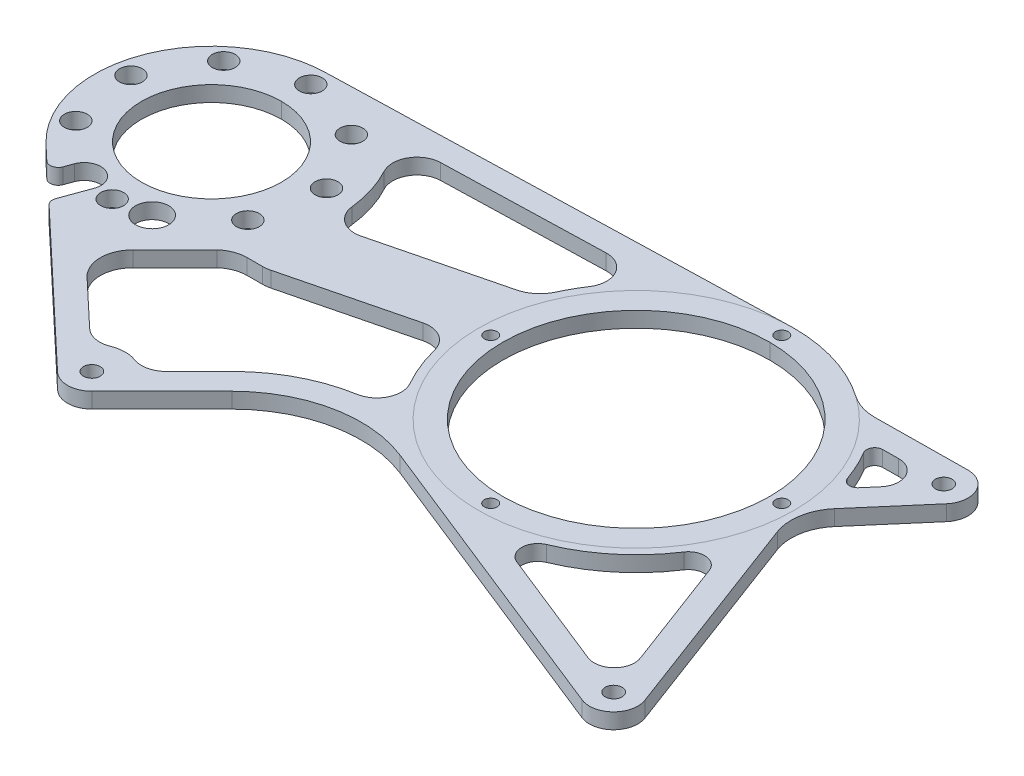
SolidWorks part; units mm, degrees
material "6061-T6 (SS)"
ref_plane "X-Y Datum" through (0, 0, 0) normal (0, 0, 1) x (1, 0, 0)
ref_plane "X-Z Datum" through (0, 0, 0) normal (0, 1, 0) x (1, 0, 0)
ref_plane "Y-Z Datum" through (0, 0, 0) normal (1, 0, 0) x (0, 0, -1)
sketch "Master Sketch " plane through (0, 0, 0) normal (0, 1, 0) x (1, 0, 0)
  line L0 (0, 0) -> (116.84, 0) construction
  line L1 (0, 0) -> (-54.61, 0) construction
  line L2 (116.84, 0) -> (228.6, 0) construction
  line L3 (228.6, 0) -> (228.6, 165.1) construction
  line L4 (123.19, 0) -> (123.19, 116.0018) construction
  line L5 (-54.61, 0) -> (-414.02, 0) construction
  line L6 (-54.61, 0) -> (-54.61, 127) construction
  line L7 (123.19, 168.4528) -> (123.19, 177.9778) construction
  line L8 (123.19, 116.0018) -> (228.6, 165.1) construction
  line L9 (123.19, 116.0018) -> (228.6, 0) construction
  line L10 (0, 0) -> (123.19, 116.0018) construction
  line L11 (0, 0) -> (-54.61, 127) construction
  line L12 (-54.61, 127) -> (123.19, 116.0018) construction
  line L13 (-54.61, 127) -> (228.6, 165.1) construction
  line L14 (0, 0) -> (0, 123.622) construction
  line L15 (-86.1521, 93.553) -> (-6.535, 18.4704)
  line L16 (-54.61, 172.974) -> (123.19, 177.9778)
  line L17 (192.5164, 124.5578) -> (212.8001, 148.1685)
  line L18 (169.599, 163.5141) -> (205.4727, 163.8999)
  line L19 (189.1339, 105.4429) -> (220.4344, 22.1488)
  line L20 (6.7352, 18.6648) -> (34.256, 46.1856)
  line L21 (207.987, 9.9519) -> (89.0101, 57.4446)
  circle A0 centre (0, 0) radius 12.7 construction
  circle A1 centre (228.6, 165.1) radius 12.7 construction
  circle A2 centre (228.6, 0) radius 12.7 construction
  circle A3 centre (-414.02, 0) radius 12.7 construction
  circle A4 centre (123.19, 116.0018) radius 52.451
  circle A5 centre (123.19, 116.0018) radius 57.15 construction
  circle A6 centre (123.19, 116.0018) radius 61.976 construction
  circle A7 centre (-54.61, 127) radius 45.974
  circle A8 centre (-54.61, 127) radius 39 construction
  circle A9 centre (205.5752, 154.3754) radius 3 construction
  circle A10 centre (211.5182, 18.7982) radius 3 construction
  circle A11 centre (0, 25.4) radius 3 construction
  circle A12 centre (0, 25.4) radius 9.525
  circle A13 centre (211.5182, 18.7982) radius 9.525
  circle A14 centre (205.5752, 154.3754) radius 9.525
  circle A15 centre (-67.9488, 90.352) radius 6.5
  circle A16 centre (-41.2712, 90.352) radius 6.5
  arc A17 (56.2619, 120.1418) -> (168.2859, 66.3745) centre (123.19, 116.0018) ccw construction
  arc A18 (123.19, 177.9778) -> (158.5311, 166.9138) centre (123.19, 116.0018) cw
  circle A19 centre (123.19, 116.0018) radius 67.056 construction
  arc A20 (192.5164, 124.5578) -> (189.1339, 105.4429) centre (206.9663, 112.1441) ccw
  arc A21 (169.599, 163.5141) -> (158.5311, 166.9138) centre (169.3942, 182.563) cw
  arc A22 (89.0101, 57.4446) -> (34.256, 46.1856) centre (70.177, 10.2646) ccw
  circle A23 centre (-54.61, 127) radius 25.908 construction
  circle A24 centre (-54.61, 127) radius 27.4955
  circle A25 centre (123.19, 173.1518) radius 2.5 construction
  point P9 (123.19, 0)
  point P23 (-54.61, 166)
  point P27 (-41.2712, 163.648)
  point P28 (-29.5413, 156.8757)
  point P29 (-20.835, 146.5)
  point P30 (-16.2025, 133.7723)
  point P31 (-16.2025, 120.2277)
  point P32 (-20.835, 107.5)
  point P33 (-29.5413, 97.1243)
  point P34 (-41.2712, 90.352)
  point P35 (-54.61, 88)
  point P36 (-67.9488, 90.352)
  point P37 (-79.6787, 97.1243)
  point P38 (-88.385, 107.5)
  point P39 (-93.0175, 120.2277)
  point P40 (-93.0175, 133.7723)
  point P41 (-88.385, 146.5)
  point P42 (-79.6787, 156.8757)
  point P43 (-67.9488, 163.648)
  point P44 (-54.61, 127)
  point P66 (190.246, 116.0018)
  point P74 (185.166, 116.0018)
  point P77 (163.0683, 163.4438)
  point P80 (74.3713, 70.0317)
  dimension "D1" = 105.41
  dimension "D2" = 25.4
  dimension "D8" = 116.0018
  dimension "D11" = 104.902
  dimension "D12" = 114.3
  dimension "D13" = 123.952
  dimension "D14" = 91.948
  dimension "D15" = 78
  dimension "D17" = 6
  dimension "D21" = 19.05
  dimension "D23" = 13
  dimension "D25" = 19.05
  dimension "D26" = 19.05
  dimension "D27" = 50.8
  dimension "D28" = 1.5875
  dimension "D30" = 51.816
  dimension "D31" = 5
  dimension "D3" = 165.1
  dimension "D4" = 171.45
  dimension "D5" = 111.76
  dimension "D6" = 116.84
  dimension "D7" = 54.61
  dimension "D9" = 642.62
  dimension "D10" = 127
  dimension "D18" = 25.4
  dimension "D19" = 25.4
  dimension "D20" = 25.4
  dimension "D22" = 228.6
  dimension "D29" = 45
  dimension "D24" = 5.08
  dimension "D16" = 18
extrude "Boss-Extrude2" add sketch "Master Sketch " along normal mid plane 6.096
hole_wizard "Ø5.0mm Dowel Hole1" positions "Sketch26" profile "Sketch27" hole size "Ø5.0" standard "ANSI Metric" end condition through all
sketch "Sketch26" plane through (0, 3.048, 0) normal (0, 1, 0) x (1, 0, 0)
  point P5 (123.19, 173.1518)
sketch "Sketch27" plane through (123.19, 3.048, -173.1518) normal (1, 0, 0) x (0, 0, 1)
  line L0 (0, 0) -> (0, 6.096)
  line L1 (0, 6.096) -> (2.5, 6.096)
  line L2 (2.5, 6.096) -> (2.5, 0)
  line L5 (2.5, 0) -> (0, 0)
  line L11 (0, -6.35) -> (0, 107.95) construction
  dimension "Thru Hole Dia." = 5
  dimension "Thru Hole Depth" = 6.096
pattern_circular "CirPattern4" count 4 over 360 about axis through (123.19, 0, -116.0018) along (0, 1, 0) of "Ø5.0mm Dowel Hole1"
hole_wizard "M6 Clearance Hole4" positions "Sketch20" profile "Sketch21" hole size "M6" standard "ANSI Metric" end condition through all
sketch "Sketch20" plane through (0, 3.048, 0) normal (0, 1, 0) x (1, 0, 0)
  point P0 (205.5752, 154.3754)
  point P3 (211.5182, 18.7982)
  point P6 (0, 25.4)
  point P9 (205.5752, 154.3754)
sketch "Sketch21" plane through (205.5752, 3.048, -154.3754) normal (1, 0, 0) x (0, 0, 1)
  line L0 (0, 0) -> (0, 6.096)
  line L1 (0, 6.096) -> (3.3, 6.096)
  line L2 (3.3, 6.096) -> (3.3, 0)
  line L5 (3.3, 0) -> (0, 0)
  line L11 (0, -6.35) -> (0, 107.95) construction
  dimension "Thru Hole Dia." = 6.6
  dimension "Thru Hole Depth" = 6.096
hole_wizard "M8 Clearance Hole1" positions "Sketch24" profile "Sketch25" hole size "M8" standard "ANSI Metric" end condition through all
sketch "Sketch24" plane through (0, 3.048, 0) normal (0, 1, 0) x (1, 0, 0)
  point P2 (-54.61, 166)
sketch "Sketch25" plane through (-54.61, 3.048, -166) normal (1, 0, 0) x (0, 0, 1)
  line L0 (0, 0) -> (0, 6.096)
  line L1 (0, 6.096) -> (4.5, 6.096)
  line L2 (4.5, 6.096) -> (4.5, 0)
  line L5 (4.5, 0) -> (0, 0)
  line L11 (0, -6.35) -> (0, 107.95) construction
  dimension "Thru Hole Dia." = 9
  dimension "Thru Hole Depth" = 6.096
pattern_circular "CirPattern3" count 18 over 360 about axis through (-54.61, 3.048, -127) along (0, -1, 0) skipping 1, 3, 5, 7, 8, 10, 11, 13, 15, 17 of "M8 Clearance Hole1"
ref_plane "Plane2" through (-54.61, 0, 0) normal (1, 0, 0) x (0, 0, -1)
ref_plane "Plane1" through (123.19, 0, 0) normal (1, 0, 0) x (0, 0, -1)
split line "Split Line2"
split line "Split Line3"
ref_point "Point2"
ref_point "Point3"
sketch "Sketch28" plane through (0, 3.048, 0) normal (0, 1, 0) x (1, 0, 0)
  circle A0 centre (123.19, 116.0018) radius 61.976 construction
  circle A1 centre (123.19, 116.0018) radius 61.976
split line "Split Line4"
sketch "Topology 1" plane through (0, 3.048, 0) normal (0, 1, 0) x (1, 0, 0)
  line L0 (145.3498, 45.211) -> (198.1607, 24.1302)
  line L1 (206.4589, 32.2614) -> (188.0555, 81.2349)
  line L2 (191.5509, 154.2246) -> (182.6033, 154.1284)
  line L3 (92.5413, 66.2908) -> (211.5182, 18.7982) construction
  line L4 (211.5182, 18.7982) -> (180.2176, 102.0923) construction
  line L5 (190.6048, 136.9496) -> (196.4358, 143.737)
  line L6 (185.2915, 130.7647) -> (205.5752, 154.3754) construction
  line L7 (205.5752, 154.3754) -> (169.7015, 153.9896) construction
  line L8 (6.7352, 18.6648) -> (34.256, 46.1856) construction
  line L9 (119.7044, 177.8797) -> (123.19, 177.9778) construction
  line L10 (119.7044, 177.8797) -> (123.19, 177.9778)
  line L11 (6.7352, 18.6648) -> (34.256, 46.1856)
  line L12 (11.5992, 36.9992) -> (27.5208, 52.9208)
  line L14 (-17.1171, 47.0221) -> (-17.1171, 64.5798)
  line L15 (-6.2723, 77.1436) -> (59.6042, 86.8711)
  line L16 (119.7044, 177.8797) -> (-54.61, 172.974)
  line L17 (-86.1521, 93.553) -> (-6.535, 18.4704)
  line L18 (6.7352, 18.6648) -> (34.256, 46.1856)
  line L19 (89.0101, 57.4446) -> (207.987, 9.9519)
  line L20 (220.4344, 22.1488) -> (189.1339, 105.4429)
  line L21 (192.5164, 124.5578) -> (212.8001, 148.1685)
  line L22 (205.4727, 163.8999) -> (169.599, 163.5141)
  line L23 (119.7044, 177.8797) -> (-54.61, 172.974)
  line L24 (-86.1521, 93.553) -> (-6.535, 18.4704)
  line L26 (89.0101, 57.4446) -> (207.987, 9.9519)
  line L27 (220.4344, 22.1488) -> (189.1339, 105.4429)
  line L28 (192.5164, 124.5578) -> (212.8001, 148.1685)
  line L29 (205.4727, 163.8999) -> (169.599, 163.5141)
  line L30 (73.4651, 167.0496) -> (-14.7002, 164.5684)
  line L31 (-4.4748, 145.7986) -> (62.0635, 147.6712)
  line L32 (-13.1304, 37.7826) -> (-11.934, 36.6543)
  line L33 (119.9724, 168.3585) -> (-54.342, 163.4528) construction
  line L34 (0, 25.4) -> (27.5208, 52.9208) construction
  arc A0 (158.5311, 166.9138) -> (123.19, 177.9778) centre (123.19, 116.0018) ccw construction
  arc A1 (158.5311, 166.9138) -> (123.19, 177.9778) centre (123.19, 116.0018) ccw
  arc A2 (145.5002, 54.1144) -> (179.5195, 82.0197) centre (123.19, 116.0018) ccw
  arc A3 (179.5195, 82.0197) -> (188.0555, 81.2349) centre (183.5974, 79.5596) cw
  arc A4 (119.4901, 181.6837) -> (160.7037, 170.0436) centre (123.19, 116.0018) ccw construction
  arc A5 (145.5002, 54.1144) -> (145.3498, 45.211) centre (147.1154, 49.6341) ccw
  arc A6 (206.4589, 32.2614) -> (198.1607, 24.1302) centre (200.5148, 30.0277) cw
  arc A7 (172.1385, 154.0158) -> (183.7852, 129.0114) centre (123.19, 116.0018) cw
  arc A8 (158.5311, 166.9138) -> (169.599, 163.5141) centre (169.3942, 182.563) ccw
  arc A9 (119.7044, 177.8797) -> (158.5311, 166.9138) centre (123.19, 116.0018) ccw
  arc A10 (-54.61, 172.974) -> (-86.1521, 93.553) centre (-54.61, 127) ccw
  arc A11 (-6.535, 18.4704) -> (6.7352, 18.6648) centre (0, 25.4) ccw
  arc A12 (89.0101, 57.4446) -> (34.256, 46.1856) centre (70.177, 10.2646) ccw
  arc A13 (207.987, 9.9519) -> (220.4344, 22.1488) centre (211.5182, 18.7982) ccw
  arc A14 (192.5164, 124.5578) -> (189.1339, 105.4429) centre (206.9663, 112.1441) ccw
  arc A15 (212.8001, 148.1685) -> (205.4727, 163.8999) centre (205.5752, 154.3754) ccw
  arc A16 (158.5311, 166.9138) -> (169.599, 163.5141) centre (169.3942, 182.563) ccw
  arc A17 (119.7044, 177.8797) -> (158.5311, 166.9138) centre (123.19, 116.0018) ccw
  arc A18 (-54.61, 172.974) -> (-86.1521, 93.553) centre (-54.61, 127) ccw
  arc A19 (-6.535, 18.4704) -> (6.7352, 18.6648) centre (0, 25.4) ccw
  arc A21 (207.987, 9.9519) -> (220.4344, 22.1488) centre (211.5182, 18.7982) ccw
  arc A22 (192.5164, 124.5578) -> (189.1339, 105.4429) centre (206.9663, 112.1441) ccw
  arc A23 (212.8001, 148.1685) -> (205.4727, 163.8999) centre (205.5752, 154.3754) ccw
  arc A24 (179.9004, 149.3443) -> (185.2036, 137.9589) centre (123.19, 116.0018) cw
  arc A25 (175.1477, 156.3527) -> (187.5103, 129.8112) centre (123.19, 116.0018) cw construction
  arc A26 (190.6048, 136.9496) -> (185.2036, 137.9589) centre (188.1965, 139.0186) cw
  arc A27 (182.6033, 154.1284) -> (179.9004, 149.3443) centre (182.6374, 150.9535) ccw
  arc A28 (196.4358, 143.737) -> (191.5509, 154.2246) centre (191.6192, 147.875) ccw
  arc A29 (89.0101, 57.4446) -> (34.256, 46.1856) centre (70.177, 10.2646) ccw construction
  arc A30 (89.0101, 57.4446) -> (34.256, 46.1856) centre (70.177, 10.2646) ccw
  arc A31 (63.8869, 70.2607) -> (27.5208, 52.9208) centre (70.177, 10.2646) ccw
  arc A32 (7.5766, 36.6135) -> (-7.9019, 36.3867) centre (0, 25.4) ccw
  arc A33 (67.8443, 88.1113) -> (82.4046, 69.3373) centre (123.19, 116.0018) ccw
  arc A34 (65.8116, 83.8223) -> (68.3344, 79.6884) centre (123.19, 116.0018) ccw
  arc A35 (64.4419, 86.3967) -> (79.8973, 66.4686) centre (123.19, 116.0018) ccw construction
  arc A36 (-10.3254, 149.2911) -> (-17.0182, 159.3246) centre (-54.61, 127) ccw
  arc A37 (70.0507, 147.896) -> (88.6754, 167.4777) centre (123.19, 116.0018) cw
  arc A38 (67.2815, 150.6721) -> (75.8397, 161.6717) centre (123.19, 116.0018) cw
  arc A39 (66.7839, 149.8567) -> (86.5536, 170.6422) centre (123.19, 116.0018) cw construction
  arc A40 (-17.0182, 159.3246) -> (-14.7002, 164.5684) centre (-14.6109, 161.3947) cw
  arc A41 (92.5413, 66.2908) -> (27.5208, 52.9208) centre (70.177, 10.2646) ccw construction
  arc A42 (-10.3254, 149.2911) -> (-4.4748, 145.7986) centre (-4.6534, 152.1461) ccw
  arc A43 (67.2815, 150.6721) -> (62.0635, 147.6712) centre (61.8849, 154.0187) cw
  arc A44 (75.8397, 161.6717) -> (73.4651, 167.0496) centre (73.5544, 163.8759) ccw
  arc A45 (-6.2723, 77.1436) -> (-17.1171, 64.5798) centre (-4.4171, 64.5798) ccw
  arc A46 (-17.1171, 47.0221) -> (-13.1304, 37.7826) centre (-4.4171, 47.0221) ccw
  arc A47 (7.5766, 36.6135) -> (11.5992, 36.9992) centre (9.3541, 39.2442) ccw
  arc A48 (-7.9019, 36.3867) -> (-11.934, 36.6543) centre (-9.7557, 38.9642) cw
  arc A49 (65.8116, 83.8223) -> (59.6042, 86.8711) centre (60.4947, 80.8405) ccw
  arc A50 (68.3344, 79.6884) -> (63.8869, 70.2607) centre (63.2512, 76.3235) cw
  point P69 (-79.6171, 100.4826)
  point P105 (-17.1171, 75.5422)
  point P108 (-17.1171, 41.5422)
  dimension "D4" = 4.7625
  dimension "D5" = 6.35
  dimension "D8" = 3.175
  dimension "D9" = 6.35
  dimension "D11" = 3.175
  dimension "D17" = 6.35
  dimension "D18" = 6.35
  dimension "D19" = 3.175
  dimension "D20" = 12.7
  dimension "D21" = 12.7
  dimension "D22" = 3.175
  dimension "D23" = 6.096
  dimension "D24" = 49.5784
  dimension "D25" = 13.5331
  dimension "D14" = 19.05
  dimension "D15" = 34
  dimension "D1" = 0
  dimension "D2" = 9.525
  dimension "D3" = 3.81
  dimension "D6" = 9.525
  dimension "D7" = 3.81
  dimension "D10" = 9.525
  dimension "D12" = 3.81
  dimension "D13" = 9.525
  dimension "D16" = 3.81
sketch "Topology 3" plane through (0, 3.048, 0) normal (0, 1, 0) x (1, 0, 0)
  line L0 (148.2326, 44.0603) -> (194.8213, 25.4632)
  line L1 (205.1941, 35.6272) -> (188.9001, 78.9873)
  line L2 (188.0448, 154.1869) -> (181.8702, 154.1205)
  line L3 (190.1271, 136.3935) -> (194.151, 141.0774)
  line L4 (185.2915, 130.7647) -> (205.5752, 154.3754) construction
  line L5 (14.5483, 39.9483) -> (27.5208, 52.9208)
  line L6 (-33.0328, 56.5514) -> (-14.9683, 39.5158)
  line L7 (119.7044, 177.8797) -> (-54.61, 172.974)
  line L8 (-86.1521, 93.553) -> (-6.535, 18.4704)
  line L9 (6.7352, 18.6648) -> (34.256, 46.1856)
  line L10 (89.0101, 57.4446) -> (207.987, 9.9519)
  line L11 (220.4344, 22.1488) -> (189.1339, 105.4429)
  line L12 (192.5164, 124.5578) -> (212.8001, 148.1685)
  line L13 (205.4727, 163.8999) -> (169.599, 163.5141)
  line L14 (119.7044, 177.8797) -> (-54.61, 172.974)
  line L15 (-86.1521, 93.553) -> (-6.535, 18.4704)
  line L16 (6.7352, 18.6648) -> (34.256, 46.1856)
  line L17 (89.0101, 57.4446) -> (207.987, 9.9519)
  line L18 (220.4344, 22.1488) -> (189.1339, 105.4429)
  line L19 (192.5164, 124.5578) -> (212.8001, 148.1685)
  line L20 (205.4727, 163.8999) -> (169.599, 163.5141)
  line L21 (-8.2138, 94.6203) -> (-2.2782, 94.6203)
  line L22 (0.802, 94.9995) -> (48.4864, 106.9206)
  line L23 (60.6168, 166.688) -> (-2.5588, 164.9101)
  line L24 (6.8654, 124.2941) -> (55.6731, 136.4961)
  line L25 (-33.2997, 74.7712) -> (-16.7203, 91.3506)
  line L26 (119.9724, 168.3585) -> (-54.342, 163.4528) construction
  line L27 (-79.6171, 100.4826) -> (0, 25.4) construction
  line L28 (0, 25.4) -> (27.5208, 52.9208) construction
  line L29 (92.5413, 66.2908) -> (211.5182, 18.7982) construction
  line L30 (211.5182, 18.7982) -> (180.2176, 102.0923) construction
  line L32 (205.5752, 154.3754) -> (169.7015, 153.9896) construction
  arc A0 (123.19, 54.0258) -> (182.1581, 96.9285) centre (123.19, 116.0018) ccw
  arc A1 (148.1536, 55.8231) -> (177.6482, 80.2392) centre (123.19, 116.0018) ccw
  arc A2 (172.1385, 154.0158) -> (183.7852, 129.0114) centre (123.19, 116.0018) cw
  arc A3 (179.1759, 149.3219) -> (184.7202, 137.4188) centre (123.19, 116.0018) cw
  arc A4 (59.8962, 69.7071) -> (27.5208, 52.9208) centre (70.177, 10.2646) ccw
  arc A5 (4.5307, 37.742) -> (-4.8904, 37.6039) centre (0, 25.4) ccw
  arc A7 (61.4889, 110.1712) -> (82.4046, 69.3373) centre (123.19, 116.0018) ccw
  arc A8 (158.5311, 166.9138) -> (169.599, 163.5141) centre (169.3942, 182.563) ccw
  arc A9 (119.7044, 177.8797) -> (158.5311, 166.9138) centre (123.19, 116.0018) ccw
  arc A10 (-54.61, 172.974) -> (-86.1521, 93.553) centre (-54.61, 127) ccw
  arc A11 (-6.535, 18.4704) -> (6.7352, 18.6648) centre (0, 25.4) ccw
  arc A12 (89.0101, 57.4446) -> (34.256, 46.1856) centre (70.177, 10.2646) ccw
  arc A13 (207.987, 9.9519) -> (220.4344, 22.1488) centre (211.5182, 18.7982) ccw
  arc A14 (192.5164, 124.5578) -> (189.1339, 105.4429) centre (206.9663, 112.1441) ccw
  arc A15 (212.8001, 148.1685) -> (205.4727, 163.8999) centre (205.5752, 154.3754) ccw
  arc A16 (158.5311, 166.9138) -> (169.599, 163.5141) centre (169.3942, 182.563) ccw
  arc A17 (119.7044, 177.8797) -> (158.5311, 166.9138) centre (123.19, 116.0018) ccw
  arc A18 (-54.61, 172.974) -> (-86.1521, 93.553) centre (-54.61, 127) ccw
  arc A19 (-6.535, 18.4704) -> (6.7352, 18.6648) centre (0, 25.4) ccw
  arc A20 (89.0101, 57.4446) -> (34.256, 46.1856) centre (70.177, 10.2646) ccw
  arc A21 (207.987, 9.9519) -> (220.4344, 22.1488) centre (211.5182, 18.7982) ccw
  arc A22 (192.5164, 124.5578) -> (189.1339, 105.4429) centre (206.9663, 112.1441) ccw
  arc A23 (212.8001, 148.1685) -> (205.4727, 163.8999) centre (205.5752, 154.3754) ccw
  arc A24 (60.0304, 100.017) -> (66.5532, 83.8005) centre (123.19, 116.0018) ccw
  arc A25 (63.439, 132.459) -> (88.6754, 167.4777) centre (123.19, 116.0018) cw
  arc A26 (64.1096, 143.4637) -> (68.8318, 151.9162) centre (123.19, 116.0018) cw
  arc A27 (-4.9122, 132.4891) -> (-10.6628, 150.8462) centre (-54.61, 127) ccw
  arc A28 (92.5413, 66.2908) -> (27.5208, 52.9208) centre (70.177, 10.2646) ccw construction
  arc A29 (58.328, 109.8725) -> (80.3152, 66.9467) centre (123.19, 116.0018) ccw construction
  arc A30 (60.378, 133.3021) -> (86.9072, 170.1148) centre (123.19, 116.0018) cw construction
  arc A31 (123.19, 50.8508) -> (185.179, 95.9514) centre (123.19, 116.0018) ccw construction
  arc A32 (174.6461, 155.9633) -> (186.8894, 129.6779) centre (123.19, 116.0018) cw construction
  arc A33 (205.1941, 35.6272) -> (194.8213, 25.4632) centre (197.7639, 32.8351) cw
  arc A34 (188.9001, 78.9873) -> (177.6482, 80.2392) centre (182.956, 76.7536) ccw
  arc A35 (148.1536, 55.8231) -> (148.2326, 44.0603) centre (150.5867, 49.9578) ccw
  arc A36 (184.7202, 137.4188) -> (190.1271, 136.3935) centre (187.7188, 138.4625) ccw
  arc A37 (181.8702, 154.1205) -> (179.1759, 149.3219) centre (181.9043, 150.9457) ccw
  arc A38 (194.151, 141.0774) -> (188.0448, 154.1869) centre (188.1302, 146.2498) ccw
  arc A39 (14.5483, 39.9483) -> (4.5307, 37.742) centre (7.8131, 46.6835) cw
  arc A40 (-4.8904, 37.6039) -> (-14.9683, 39.5158) centre (-8.4334, 46.4454) cw
  arc A42 (48.4864, 106.9206) -> (60.0304, 100.017) centre (50.7965, 97.68) cw
  arc A43 (59.8962, 69.7071) -> (66.5532, 83.8005) centre (58.2729, 79.0927) ccw
  arc A44 (-2.2782, 94.6203) -> (0.802, 94.9995) centre (-2.2782, 107.3203) ccw
  arc A45 (-16.7203, 91.3506) -> (-8.2138, 94.6203) centre (-8.2138, 81.9203) cw
  arc A46 (-2.5588, 164.9101) -> (-10.6628, 150.8462) centre (-2.2908, 155.3889) ccw
  arc A47 (6.8654, 124.2941) -> (-4.9122, 132.4891) centre (4.5552, 133.5347) cw
  arc A48 (55.6731, 136.4961) -> (64.1096, 143.4637) centre (52.5929, 148.8169) ccw
  arc A49 (68.8318, 151.9162) -> (60.6168, 166.688) centre (60.8847, 157.1668) ccw
  arc A50 (-33.2997, 74.7712) -> (-33.0328, 56.5514) centre (-24.3195, 65.7909) ccw
  dimension "D11" = 7.9375
  dimension "D12" = 6.35
  dimension "D13" = 3.175
  dimension "D14" = 7.9375
  dimension "D15" = 9.525
  dimension "D16" = 12.7
  dimension "D17" = 9.525
  dimension "D18" = 12.7
  dimension "D19" = 12.7
  dimension "D21" = 9.525
  dimension "D22" = 9.525
  dimension "D23" = 12.7
  dimension "D24" = 9.525
  dimension "D25" = 50
  dimension "D27" = 65.151
  dimension "D28" = 65.151
  dimension "D29" = 65.151
  dimension "D30" = 65.151
  dimension "D20" = 26.9494
  dimension "D26" = 52
  dimension "D1" = 0
  dimension "D2" = 9.525
  dimension "D3" = 3.175
  dimension "D4" = 9.525
  dimension "D5" = 3.175
  dimension "D6" = 9.525
  dimension "D7" = 9.525
  dimension "D8" = 3.175
  dimension "D9" = 9.525
  dimension "D10" = 3.175
sketch "Topology (50%)" plane through (0, 3.048, 0) normal (0, 1, 0) x (1, 0, 0)
  line L0 (-37.2011, 60.4823) -> (-14.9683, 39.5158)
  line L2 (188.0448, 154.1869) -> (181.8702, 154.1205)
  line L3 (190.1271, 136.3935) -> (194.151, 141.0774)
  line L4 (188.0448, 154.1869) -> (181.8702, 154.1205)
  line L5 (190.1271, 136.3935) -> (194.151, 141.0774)
  line L6 (148.2326, 44.0603) -> (194.8213, 25.4632)
  line L7 (192.5164, 124.5578) -> (212.8001, 148.1685)
  line L8 (220.4344, 22.1488) -> (189.1339, 105.4429)
  line L9 (89.0101, 57.4446) -> (207.987, 9.9519)
  line L10 (6.7352, 18.6648) -> (34.256, 46.1856)
  line L11 (-86.1521, 93.553) -> (-6.535, 18.4704)
  line L12 (119.7044, 177.8797) -> (-54.61, 172.974)
  line L13 (205.4727, 163.8999) -> (169.599, 163.5141)
  line L14 (192.5164, 124.5578) -> (212.8001, 148.1685)
  line L15 (220.4344, 22.1488) -> (189.1339, 105.4429)
  line L16 (89.0101, 57.4446) -> (207.987, 9.9519)
  line L17 (6.7352, 18.6648) -> (34.256, 46.1856)
  line L18 (-86.1521, 93.553) -> (-6.535, 18.4704)
  line L19 (119.7044, 177.8797) -> (-54.61, 172.974)
  line L20 (205.4727, 163.8999) -> (169.599, 163.5141)
  line L21 (205.1941, 35.6272) -> (188.9001, 78.9873)
  line L22 (148.2326, 44.0603) -> (194.8213, 25.4632)
  line L23 (205.1941, 35.6272) -> (188.9001, 78.9873)
  line L24 (60.6168, 166.688) -> (-2.5588, 164.9101)
  line L25 (6.8654, 124.2941) -> (55.6731, 136.4961)
  line L26 (60.6168, 166.688) -> (-2.5588, 164.9101)
  line L27 (-33.0328, 56.5514) -> (-14.9683, 39.5158)
  line L28 (14.5483, 39.9483) -> (27.5208, 52.9208)
  line L29 (48.4864, 106.9206) -> (0.802, 94.9995)
  line L30 (-2.2782, 94.6203) -> (-8.2138, 94.6203)
  line L31 (-17.6441, 90.4268) -> (-33.2997, 74.7712)
  line L33 (14.5483, 39.9483) -> (27.5208, 52.9208)
  arc A0 (123.19, 54.0258) -> (182.1581, 96.9285) centre (123.19, 116.0018) ccw construction
  arc A1 (183.7852, 129.0114) -> (172.1385, 154.0158) centre (123.19, 116.0018) ccw construction
  arc A2 (61.4889, 110.1712) -> (82.4046, 69.3373) centre (123.19, 116.0018) ccw construction
  arc A3 (88.6754, 167.4777) -> (63.439, 132.459) centre (123.19, 116.0018) ccw construction
  arc A4 (181.8702, 154.1205) -> (179.1759, 149.3219) centre (181.9043, 150.9457) ccw
  arc A5 (184.7202, 137.4188) -> (179.1759, 149.3219) centre (123.19, 116.0018) ccw
  arc A6 (184.7202, 137.4188) -> (190.1271, 136.3935) centre (187.7188, 138.4625) ccw
  arc A7 (194.151, 141.0774) -> (188.0448, 154.1869) centre (188.1302, 146.2498) ccw
  arc A8 (192.5164, 124.5578) -> (189.1339, 105.4429) centre (206.9663, 112.1441) ccw
  arc A9 (207.987, 9.9519) -> (220.4344, 22.1488) centre (211.5182, 18.7982) ccw
  arc A10 (89.0101, 57.4446) -> (34.256, 46.1856) centre (70.177, 10.2646) ccw
  arc A11 (-6.535, 18.4704) -> (6.7352, 18.6648) centre (0, 25.4) ccw
  arc A12 (-54.61, 172.974) -> (-86.1521, 93.553) centre (-54.61, 127) ccw
  arc A13 (119.7044, 177.8797) -> (158.5311, 166.9138) centre (123.19, 116.0018) ccw
  arc A14 (158.5311, 166.9138) -> (169.599, 163.5141) centre (169.3942, 182.563) ccw
  arc A15 (212.8001, 148.1685) -> (205.4727, 163.8999) centre (205.5752, 154.3754) ccw
  arc A16 (192.5164, 124.5578) -> (189.1339, 105.4429) centre (206.9663, 112.1441) ccw
  arc A17 (207.987, 9.9519) -> (220.4344, 22.1488) centre (211.5182, 18.7982) ccw
  arc A18 (89.0101, 57.4446) -> (34.256, 46.1856) centre (70.177, 10.2646) ccw
  arc A19 (-6.535, 18.4704) -> (6.7352, 18.6648) centre (0, 25.4) ccw
  arc A20 (-54.61, 172.974) -> (-86.1521, 93.553) centre (-54.61, 127) ccw
  arc A21 (119.7044, 177.8797) -> (158.5311, 166.9138) centre (123.19, 116.0018) ccw
  arc A22 (158.5311, 166.9138) -> (169.599, 163.5141) centre (169.3942, 182.563) ccw
  arc A23 (212.8001, 148.1685) -> (205.4727, 163.8999) centre (205.5752, 154.3754) ccw
  arc A24 (181.8702, 154.1205) -> (179.1759, 149.3219) centre (181.9043, 150.9457) ccw
  arc A25 (184.7202, 137.4188) -> (179.1759, 149.3219) centre (123.19, 116.0018) ccw
  arc A26 (184.7202, 137.4188) -> (190.1271, 136.3935) centre (187.7188, 138.4625) ccw
  arc A27 (194.151, 141.0774) -> (188.0448, 154.1869) centre (188.1302, 146.2498) ccw
  arc A28 (194.8213, 25.4632) -> (205.1941, 35.6272) centre (197.7639, 32.8351) ccw
  arc A29 (188.9001, 78.9873) -> (177.6482, 80.2392) centre (182.956, 76.7536) ccw
  arc A30 (148.1536, 55.8231) -> (177.6482, 80.2392) centre (123.19, 116.0018) ccw
  arc A31 (148.1536, 55.8231) -> (148.2326, 44.0603) centre (150.5867, 49.9578) ccw
  arc A32 (194.8213, 25.4632) -> (205.1941, 35.6272) centre (197.7639, 32.8351) ccw
  arc A33 (188.9001, 78.9873) -> (177.6482, 80.2392) centre (182.956, 76.7536) ccw
  arc A34 (148.1536, 55.8231) -> (177.6482, 80.2392) centre (123.19, 116.0018) ccw
  arc A35 (148.1536, 55.8231) -> (148.2326, 44.0603) centre (150.5867, 49.9578) ccw
  arc A36 (123.19, 54.0258) -> (182.1581, 96.9285) centre (123.19, 116.0018) ccw
  arc A37 (183.7852, 129.0114) -> (172.1385, 154.0158) centre (123.19, 116.0018) ccw
  arc A38 (-2.5588, 164.9101) -> (-10.6628, 150.8462) centre (-2.2908, 155.3889) ccw
  arc A39 (-4.9122, 132.4891) -> (-10.6628, 150.8462) centre (-54.61, 127) ccw
  arc A40 (-4.9122, 132.4891) -> (6.8654, 124.2941) centre (4.5552, 133.5347) ccw
  arc A41 (55.6731, 136.4961) -> (64.1096, 143.4637) centre (52.5929, 148.8169) ccw
  arc A42 (-14.9683, 39.5158) -> (-4.8904, 37.6039) centre (-8.4334, 46.4454) ccw
  arc A43 (4.5307, 37.742) -> (-4.8904, 37.6039) centre (0, 25.4) ccw
  arc A44 (4.5307, 37.742) -> (14.5483, 39.9483) centre (7.8131, 46.6835) ccw
  arc A45 (59.8962, 69.7071) -> (27.5208, 52.9208) centre (70.177, 10.2646) ccw
  arc A46 (59.8962, 69.7071) -> (66.5532, 83.8005) centre (58.2729, 79.0927) ccw
  arc A47 (60.0304, 100.017) -> (66.5532, 83.8005) centre (123.19, 116.0018) ccw
  arc A48 (60.0304, 100.017) -> (48.4864, 106.9206) centre (50.7965, 97.68) ccw
  arc A49 (-2.2782, 94.6203) -> (0.802, 94.9995) centre (-2.2782, 107.3203) ccw
  arc A50 (-8.2138, 94.6203) -> (-17.6441, 90.4268) centre (-8.2138, 81.9203) ccw
  arc A52 (-14.9683, 39.5158) -> (-4.8904, 37.6039) centre (-8.4334, 46.4454) ccw
  arc A53 (4.5307, 37.742) -> (-4.8904, 37.6039) centre (0, 25.4) ccw
  arc A54 (4.5307, 37.742) -> (14.5483, 39.9483) centre (7.8131, 46.6835) ccw
  arc A55 (59.8962, 69.7071) -> (27.5208, 52.9208) centre (70.177, 10.2646) ccw
  arc A56 (59.8962, 69.7071) -> (66.5532, 83.8005) centre (58.2729, 79.0927) ccw
  arc A57 (60.0304, 100.017) -> (66.5532, 83.8005) centre (123.19, 116.0018) ccw
  arc A62 (68.8318, 151.9162) -> (64.1096, 143.4637) centre (123.19, 116.0018) ccw
  arc A63 (68.8318, 151.9162) -> (60.6168, 166.688) centre (60.8847, 157.1668) ccw
  arc A64 (-2.5588, 164.9101) -> (-10.6628, 150.8462) centre (-2.2908, 155.3889) ccw
  arc A65 (-4.9122, 132.4891) -> (-10.6628, 150.8462) centre (-54.61, 127) ccw
  arc A69 (68.8318, 151.9162) -> (60.6168, 166.688) centre (60.8847, 157.1668) ccw
  arc A70 (61.4889, 110.1712) -> (82.4046, 69.3373) centre (123.19, 116.0018) ccw
  arc A71 (88.6754, 167.4777) -> (63.439, 132.459) centre (123.19, 116.0018) ccw
  arc A72 (-33.9402, 81.4724) -> (-10.6628, 150.8462) centre (-54.61, 127) ccw
  arc A73 (148.1536, 55.8231) -> (177.6482, 80.2392) centre (123.19, 116.0018) ccw
  arc A74 (68.8318, 151.9162) -> (66.5532, 83.8005) centre (123.19, 116.0018) ccw
  arc A75 (184.7202, 137.4188) -> (179.1759, 149.3219) centre (123.19, 116.0018) ccw
  arc A76 (188.0521, 109.8735) -> (188.3408, 116.1433) centre (123.19, 116.0018) ccw
  arc A77 (-37.2011, 60.4823) -> (-33.9402, 81.4724) centre (-28.69, 69.9085) cw
  arc A88 (-33.2997, 74.7712) -> (-33.0328, 56.5514) centre (-24.3195, 65.7909) ccw
  dimension "D6" = 12.7
  dimension "D8" = 30.5597
  dimension "D1" = 0
  dimension "D2" = 0
  dimension "D3" = 0
  dimension "D4" = 0
  dimension "D5" = 0
extrude "Cut-Extrude1" [suppressed] cut sketch "Topology 1" against normal through all contours A38 A44 L30 A40 A36 A42 L31 A43 | A50 A34 A49 L15 A45 L14 A46 L32 A48 A32 A47 L12 A31 | A6 L1 A3 A2 A5 L0 | L5 A28 L2 A27 A24 A26
extrude "Cut-Extrude2" cut sketch "Topology 3" against normal through all
extrude "Cut-Extrude3" [suppressed] cut sketch "Topology (50%)" against normal through all contours A77 L0 A52 A53 A54 L33 A55 A56 A57 A74 A69 L26 A64 A65 A72 | A34 A35 L22 A32 L23 A33 | L5 A27 L4 A24 A25 A26
sketch "Sketch29" plane through (0, 3.048, 0) normal (0, 1, 0) x (1, 0, 0)
  line L0 (-86.1521, 93.553) -> (-6.535, 18.4704)
  line L1 (-54.61, 166) -> (-54.61, 88) construction
  line L2 (-58.4616, 116.4177) -> (-77.4359, 64.2863) construction
  line L3 (-74.0568, 92.5751) -> (-76.8826, 84.8114)
  line L4 (-86.1521, 93.553) -> (-6.535, 18.4704) construction
  line L5 (-61.8408, 88.1289) -> (-66.5834, 75.0987)
  circle A0 centre (-67.9488, 90.352) radius 6.5 construction
  circle A1 centre (-67.9488, 90.352) radius 6.5
  point P6 (-54.61, 127)
  point P9 (-67.9488, 90.352)
  point P10 (-67.9488, 90.352)
  dimension "D1" = 20
extrude "Cut-Extrude4" cut sketch "Sketch29" against normal through all
fillet "Fillet1" radius 3.175 2 edges at (-66.5834, 0, -75.0987) (-76.8826, 0, -84.8114)
